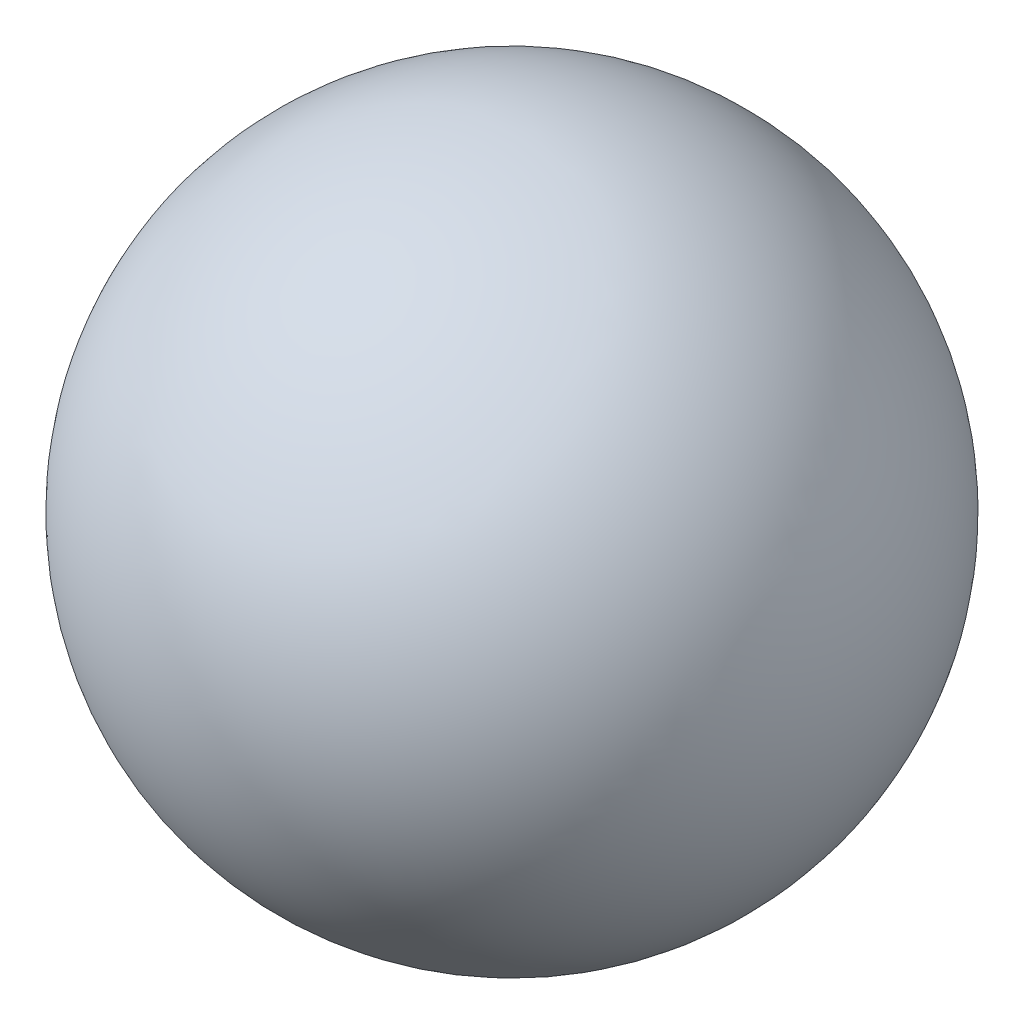
SolidWorks part; units mm, degrees
ref_plane "Front Plane" through (0, 0, 0) normal (0, 0, 1) x (1, 0, 0)
ref_plane "Top Plane" through (0, 0, 0) normal (0, 1, 0) x (1, 0, 0)
ref_plane "Right Plane" through (0, 0, 0) normal (1, 0, 0) x (0, 0, -1)
sketch "Sketch1" plane through (0, 0, 0) normal (0, 0, 1) x (1, 0, 0)
  line L0 (0, 0) -> (-4, 0)
  line L1 (0, 0) -> (4, 0)
  arc A0 (-4, 0) -> (4, 0) centre (0, 0) ccw
  dimension "D1" = 4
revolve "Revolve1" add sketch "Sketch1" angle 360 about L1
